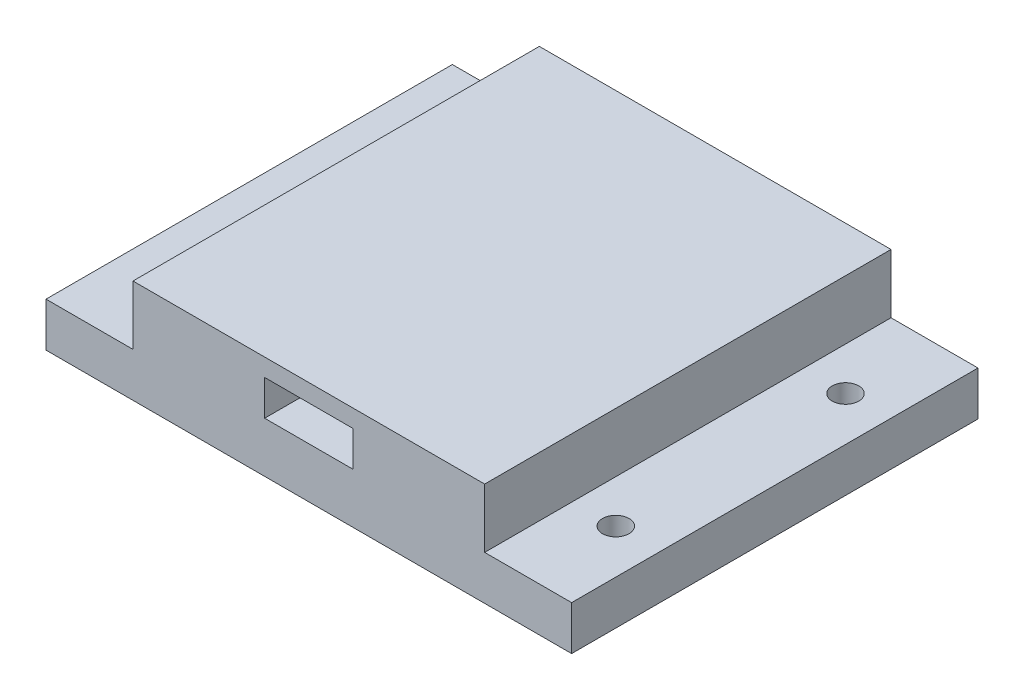
SolidWorks part; units mm, degrees
material "AISI 304"
ref_plane "前视基准面" through (0, 0, 0) normal (0, 0, 1) x (1, 0, 0)
ref_plane "上视基准面" through (0, 0, 0) normal (0, 1, 0) x (1, 0, 0)
ref_plane "右视基准面" through (0, 0, 0) normal (1, 0, 0) x (0, 0, -1)
other "Configuration Table"
sketch "草图1" plane through (0, 0, 0) normal (0, 1, 0) x (1, 0, 0)
  line L0 (0, 0) -> (0, 27.42) construction
  line L1 (-29.75, -23) -> (29.75, -23)
  line L2 (-29.75, -23) -> (-29.75, 23)
  line L3 (-29.75, 23) -> (29.75, 23)
  line L4 (29.75, -23) -> (29.75, 23)
  line L5 (-29.75, -23) -> (29.75, 23) construction
  line L6 (-29.75, 23) -> (29.75, -23) construction
  line L7 (0, 0) -> (50.693, 0) construction
  circle A0 centre (24.75, 13) radius 1.5
  circle A1 centre (24.75, -13) radius 1.5
  circle A2 centre (-24.75, -13) radius 1.5
  circle A3 centre (-24.75, 13) radius 1.5
  point P0 (0, 0)
  dimension "D3" = 3
  dimension "D4" = 26
  dimension "D5" = 49.5
  dimension "D1" = 59.5
  dimension "D2" = 46
extrude "凸台-拉伸1" add sketch "草图1" along normal blind 5
sketch "草图2" plane through (0, 5, 0) normal (0, 1, 0) x (1, 0, 0)
  line L0 (29.75, 23) -> (-29.75, 23) construction
  line L1 (-19.905, -23) -> (19.905, -23)
  line L2 (-19.905, -23) -> (-19.905, 23)
  line L3 (-19.905, 23) -> (19.905, 23)
  line L4 (19.905, -23) -> (19.905, 23)
  line L5 (-19.905, -23) -> (19.905, 23) construction
  line L6 (-19.905, 23) -> (19.905, -23) construction
  point P0 (0, 0)
  dimension "D1" = 39.81
extrude "凸台-拉伸2" add sketch "草图2" along normal blind 6.7
sketch "草图3" plane through (0, 0, 23) normal (0, 0, 1) x (1, 0, 0)
  line L0 (0, 0) -> (0, 19.2162) construction
  line L1 (-19.905, 11.7) -> (19.905, 11.7) construction
  line L2 (-5, 5.7) -> (5, 5.7)
  line L3 (-5, 5.7) -> (-5, 9.7)
  line L4 (-5, 9.7) -> (5, 9.7)
  line L5 (5, 5.7) -> (5, 9.7)
  line L6 (-5, 5.7) -> (5, 9.7) construction
  line L7 (-5, 9.7) -> (5, 5.7) construction
  point P3 (0, 7.7)
  dimension "D1" = 10
  dimension "D2" = 4
  dimension "D3" = 2
extrude "切除-拉伸1" cut sketch "草图3" against normal blind 6.7
